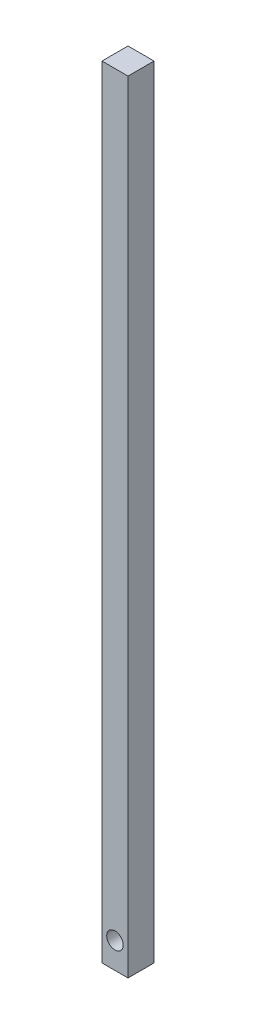
SolidWorks part; units mm, degrees
ref_plane "Front Plane" through (0, 0, 0) normal (0, 0, 1) x (1, 0, 0)
ref_plane "Top Plane" through (0, 0, 0) normal (0, 1, 0) x (1, 0, 0)
ref_plane "Right Plane" through (0, 0, 0) normal (1, 0, 0) x (0, 0, -1)
sketch "Sketch1" plane through (0, 0, 0) normal (0, 1, 0) x (1, 0, 0)
  line L1 (0, 0) -> (10, 0)
  line L2 (0, 0) -> (0, 10)
  line L3 (0, 10) -> (10, 10)
  line L4 (10, 0) -> (10, 10)
  dimension "D1" = 10
  dimension "D2" = 10
extrude "Boss-Extrude1" add sketch "Sketch1" along normal blind 300
sketch "Sketch2" plane through (0, 0, 0) normal (0, 0, 1) x (1, 0, 0)
  line L0 (0, 0) -> (10, 0) construction
  line L1 (0, 300) -> (0, 0) construction
  circle A0 centre (5, 10) radius 3.175
  dimension "D1" = 6.35
  dimension "D2" = 10
  dimension "D3" = 5
extrude "Cut-Extrude1" cut sketch "Sketch2" against normal through all
